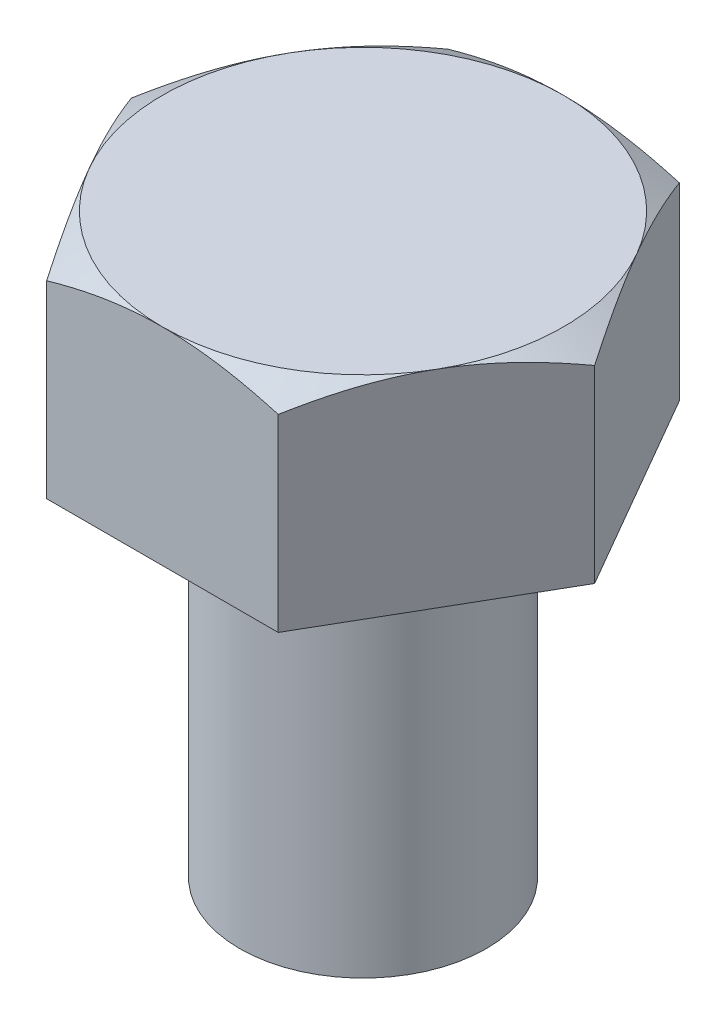
SolidWorks part; units mm, degrees
ref_plane "Front Plane" through (0, 0, 0) normal (0, 0, 1) x (1, 0, 0)
ref_plane "Top Plane" through (0, 0, 0) normal (0, 1, 0) x (1, 0, 0)
ref_plane "Right Plane" through (0, 0, 0) normal (1, 0, 0) x (0, 0, -1)
sketch "Sketch1" plane through (0, 0, 0) normal (0, 1, 0) x (1, 0, 0)
  line L1 (7.5056, 0) -> (3.7528, 6.5)
  line L2 (3.7528, 6.5) -> (-3.7528, 6.5)
  line L3 (-3.7528, 6.5) -> (-7.5056, 0)
  line L4 (-7.5056, 0) -> (-3.7528, -6.5)
  line L5 (-3.7528, -6.5) -> (3.7528, -6.5)
  line L6 (3.7528, -6.5) -> (7.5056, 0)
  circle A1 centre (0, 0) radius 6.5 construction
  dimension "D1" = 13
extrude "Boss-Extrude1" add sketch "Sketch1" along normal blind 6.7
sketch "Sketch2" plane through (0, 0, 0) normal (0, -1, 0) x (1, 0, 0)
  circle A0 centre (0, 0) radius 4
  dimension "D1" = 8
extrude "Boss-Extrude2" add sketch "Sketch2" along normal blind 12
sketch "Sketch3" plane through (0, 6.7, 0) normal (0, 1, 0) x (1, 0, 0)
  circle A0 centre (0, 0) radius 6.5
extrude "Cut-Extrude3" cut sketch "Sketch3" against normal blind 10 draft 60 flip side to cut
